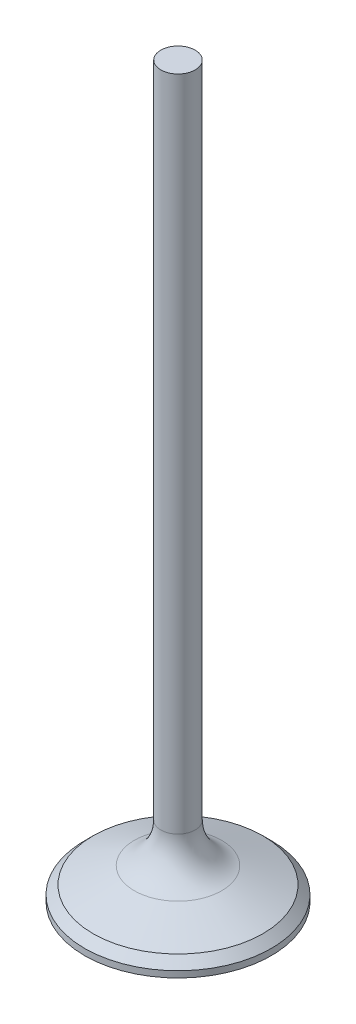
SolidWorks part; units mm, degrees
material "Chrome Stainless Steel"
ref_plane "Front Plane" through (0, 0, 0) normal (0, 0, 1) x (1, 0, 0)
ref_plane "Top Plane" through (0, 0, 0) normal (0, 1, 0) x (1, 0, 0)
ref_plane "Right Plane" through (0, 0, 0) normal (1, 0, 0) x (0, 0, -1)
sketch "Sketch1" plane through (0, 0, 0) normal (0, 0, 1) x (1, 0, 0)
  line L0 (0, 0) -> (0, 115.95) construction
  line L1 (0, 0) -> (14.85, 0)
  line L2 (14.85, 0) -> (14.85, 1)
  line L3 (14.85, 1) -> (13.5, 2.35)
  line L4 (2.73, 11.2543) -> (2.73, 115.95)
  line L5 (13.5, 2.35) -> (6.9514, 4.9958)
  line L6 (2.73, 115.95) -> (0, 115.95)
  line L7 (0, 0) -> (0, 115.95)
  arc A0 (6.9514, 4.9958) -> (2.73, 11.2543) centre (9.48, 11.2543) cw
  dimension "D7" = 6.75
  dimension "D2" = 45
  dimension "D3" = 1
  dimension "D4" = 22
  dimension "D6" = 115.95
  dimension "D5" = 27
  dimension "D1" = 5.46
  dimension "D8" = 29.7
revolve "Revolve1" add sketch "Sketch1" angle 360 about L0
equation "\"D7@Sketch1\"=.25*\"D5@Sketch1\""
equation "\"D8@Sketch1\"=1.1*\"D5@Sketch1\""
